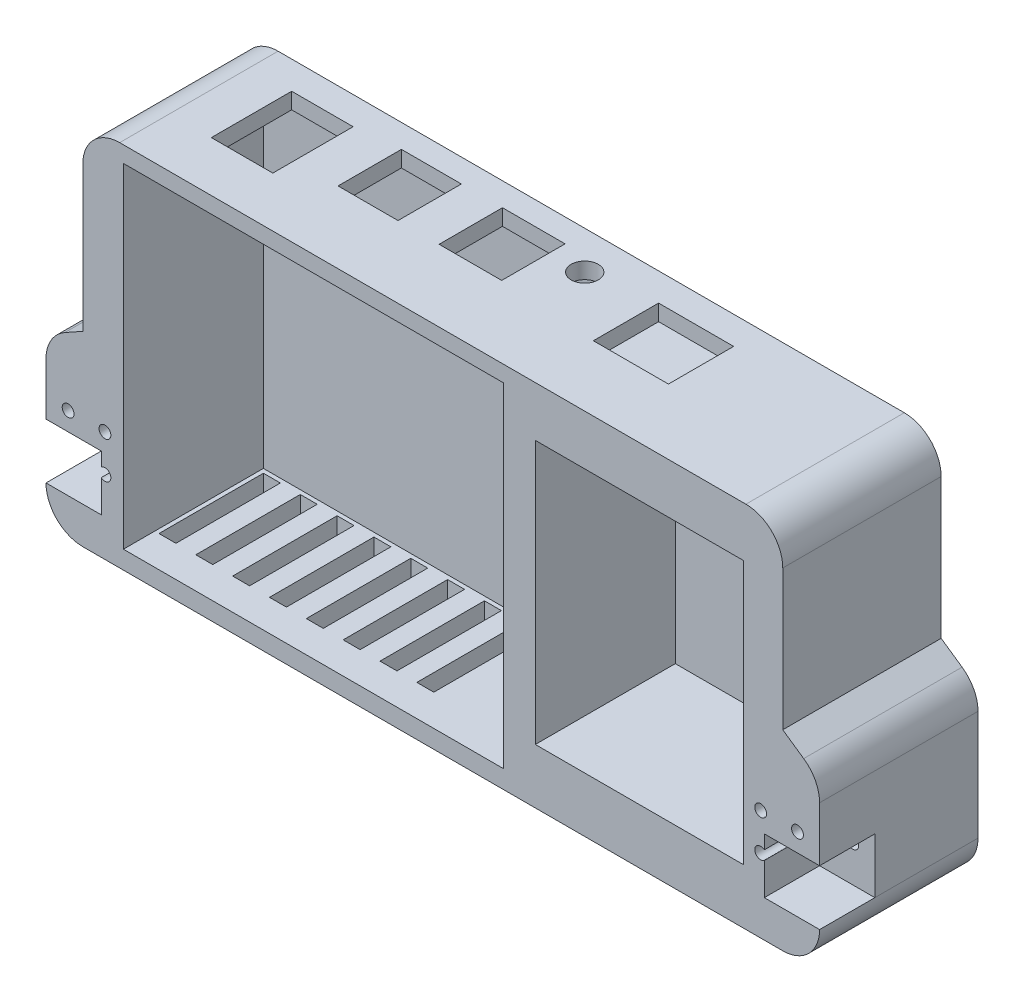
SolidWorks part; units mm, degrees
material "ABS"
ref_plane "前视基准面" through (0, 0, 0) normal (0, 0, 1) x (1, 0, 0)
ref_plane "上视基准面" through (0, 0, 0) normal (0, 1, 0) x (1, 0, 0)
ref_plane "右视基准面" through (0, 0, 0) normal (1, 0, 0) x (0, 0, -1)
other "Configuration Table"
sketch "草图1" plane through (0, 0, 0) normal (0, 0, 1) x (1, 0, 0)
  line L0 (0, 10) -> (0, 39.1866)
  line L1 (5.1248, 47.9177) -> (10, 50.6399)
  line L2 (10, 50.6399) -> (10, 90)
  line L3 (20, 100) -> (190, 100)
  line L4 (200, 90) -> (200, 51.9634)
  line L5 (200, 51.9634) -> (205.6833, 48.0378)
  line L6 (210, 39.8098) -> (210, 10)
  line L7 (200, 0) -> (10, 0)
  line L9 (21.0146, 95.6225) -> (124.2146, 95.6225)
  line L10 (21.0146, 95.6225) -> (21.0146, 4.9225)
  line L11 (21.0146, 4.9225) -> (124.2146, 4.9225)
  line L12 (124.2146, 95.6225) -> (124.2146, 4.9225)
  line L13 (132.8291, 86.4254) -> (189.3291, 86.4254)
  line L14 (132.8291, 86.4254) -> (132.8291, 14.9254)
  line L15 (132.8291, 14.9254) -> (189.3291, 14.9254)
  line L16 (189.3291, 86.4254) -> (189.3291, 14.9254)
  arc A0 (210, 10) -> (200, 0) centre (200, 10) cw
  arc A1 (0, 10) -> (10, 0) centre (10, 10) ccw
  arc A2 (205.6833, 48.0378) -> (210, 39.8098) centre (200, 39.8098) cw
  arc A3 (0, 39.1866) -> (5.1248, 47.9177) centre (10, 39.1866) cw
  arc A4 (190, 100) -> (200, 90) centre (190, 90) cw
  arc A5 (10, 90) -> (20, 100) centre (20, 90) cw
  point P13 (0, 0)
  dimension "D1" = 10
  dimension "D2" = 190
  dimension "D3" = 100
  dimension "D4" = 103.2
  dimension "D5" = 90.7
  dimension "D6" = 71.5
  dimension "D7" = 56.5
  dimension "D8" = 10
  dimension "D9" = 10
extrude "凸台-拉伸1" add sketch "草图1" along normal blind 43
sketch "草图3" plane through (0, 0, 0) normal (0, 0, 1) x (1, 0, 0)
  line L0 (0, 10) -> (0, 39.1866)
  line L1 (5.1248, 47.9177) -> (10, 50.6399)
  line L2 (10, 50.6399) -> (10, 90)
  line L3 (20, 100) -> (180, 100)
  line L4 (190, 90) -> (190, 51.9634)
  line L5 (190, 51.9634) -> (195.6833, 48.0378)
  line L6 (200, 39.8098) -> (200, 10)
  line L7 (190, 0) -> (10, 0)
  arc A0 (200, 10) -> (190, 0) centre (190, 10) cw
  arc A1 (0, 10) -> (10, 0) centre (10, 10) ccw
  arc A2 (195.6833, 48.0378) -> (200, 39.8098) centre (190, 39.8098) cw
  arc A3 (0, 39.1866) -> (5.1248, 47.9177) centre (10, 39.1866) cw
  arc A4 (180, 100) -> (190, 90) centre (180, 90) cw
  arc A5 (10, 90) -> (20, 100) centre (20, 90) cw
  point P13 (0, 0)
  dimension "D1" = 10
  dimension "D2" = 180
  dimension "D3" = 100
  dimension "D8" = 10
  dimension "D9" = 10
extrude "凸台-拉伸3" add sketch "草图3" along normal blind 5
sketch "草图4" plane through (0, 100, 0) normal (0, 1, 0) x (1, 0, 0)
  line L1 (130.8683, -7.5722) -> (151.2394, -7.5722)
  line L2 (130.8683, -7.5722) -> (130.8683, -25.2818)
  line L3 (130.8683, -25.2818) -> (151.2394, -25.2818)
  line L4 (151.2394, -7.5722) -> (151.2394, -25.2818)
  line L5 (31.2602, -7.5722) -> (47.9461, -7.5722)
  line L6 (31.2602, -7.5722) -> (31.2602, -29.3765)
  line L7 (31.2602, -29.3765) -> (47.9461, -29.3765)
  line L8 (47.9461, -7.5722) -> (47.9461, -29.3765)
  line L9 (59.8207, -6.3438) -> (76.0972, -6.3438)
  line L10 (59.8207, -6.3438) -> (59.8207, -23.5415)
  line L11 (59.8207, -23.5415) -> (76.0972, -23.5415)
  line L12 (76.0972, -6.3438) -> (76.0972, -23.5415)
  line L13 (87.2552, -6.3438) -> (104.2483, -6.3438)
  line L14 (87.2552, -6.3438) -> (87.2552, -23.5415)
  line L15 (87.2552, -23.5415) -> (104.2483, -23.5415)
  line L16 (104.2483, -6.3438) -> (104.2483, -23.5415)
  circle A0 centre (113.5637, -10.3226) radius 3.6826
extrude "切除-拉伸2" cut sketch "草图4" against normal up to surface (4.3775 mm away) up to face at (72.6146, 95.6225, 24)
sketch "草图5" plane through (0, 0, 0) normal (0, -1, 0) x (1, 0, 0)
  line L0 (32.1495, 34.485) -> (32.1495, 6.1292)
  line L1 (22.1495, 34.485) -> (26.756, 34.485)
  line L2 (22.1495, 34.485) -> (22.1495, 6.1292)
  line L3 (22.1495, 6.1292) -> (26.756, 6.1292)
  line L4 (26.756, 34.485) -> (26.756, 6.1292)
  line L5 (32.1495, 34.485) -> (36.756, 34.485)
  line L6 (36.756, 34.485) -> (36.756, 6.1292)
  line L7 (32.1495, 6.1292) -> (36.756, 6.1292)
  line L8 (42.1495, 34.485) -> (42.1495, 6.1292)
  line L9 (42.1495, 34.485) -> (46.756, 34.485)
  line L10 (46.756, 34.485) -> (46.756, 6.1292)
  line L11 (42.1495, 6.1292) -> (46.756, 6.1292)
  line L12 (52.1495, 34.485) -> (52.1495, 6.1292)
  line L13 (52.1495, 34.485) -> (56.756, 34.485)
  line L14 (56.756, 34.485) -> (56.756, 6.1292)
  line L15 (52.1495, 6.1292) -> (56.756, 6.1292)
  line L16 (62.1495, 34.485) -> (62.1495, 6.1292)
  line L17 (62.1495, 34.485) -> (66.756, 34.485)
  line L18 (66.756, 34.485) -> (66.756, 6.1292)
  line L19 (62.1495, 6.1292) -> (66.756, 6.1292)
  line L20 (72.1495, 34.485) -> (72.1495, 6.1292)
  line L21 (72.1495, 34.485) -> (76.756, 34.485)
  line L22 (76.756, 34.485) -> (76.756, 6.1292)
  line L23 (72.1495, 6.1292) -> (76.756, 6.1292)
  line L24 (82.1495, 34.485) -> (82.1495, 6.1292)
  line L25 (82.1495, 34.485) -> (86.756, 34.485)
  line L26 (86.756, 34.485) -> (86.756, 6.1292)
  line L27 (82.1495, 6.1292) -> (86.756, 6.1292)
  line L28 (92.1495, 34.485) -> (92.1495, 6.1292)
  line L29 (92.1495, 34.485) -> (96.756, 34.485)
  line L30 (96.756, 34.485) -> (96.756, 6.1292)
  line L31 (92.1495, 6.1292) -> (96.756, 6.1292)
  dimension "D1" = 8
extrude "切除-拉伸3" cut sketch "草图5" against normal up to surface (4.9225 mm away) up to face at (72.6146, 4.9225, 24)
sketch "草图7" plane through (0, 0, 43) normal (0, 0, 1) x (1, 0, 0)
  line L0 (6, 30) -> (16, 30) construction
  line L1 (6, 30) -> (6, 20) construction
  line L2 (0, 39.1866) -> (0, 10) construction
  line L3 (10, 0) -> (200, 0) construction
  line L4 (210, 10) -> (210, 39.8098) construction
  line L6 (194, 30) -> (204, 30) construction
  line L7 (194, 30) -> (194, 20) construction
  circle A11 centre (6, 30) radius 1.6
  circle A12 centre (16, 30) radius 1.6
  circle A13 centre (16, 20) radius 1.6
  circle A14 centre (6, 20) radius 1.6
  circle A19 centre (194, 30) radius 1.6
  circle A20 centre (204, 30) radius 1.6
  circle A21 centre (204, 20) radius 1.6
  circle A22 centre (194, 20) radius 1.6
  dimension "D1" = 3.2
  dimension "D4" = 6
  dimension "D6" = 30
  dimension "D9" = 3.2
  dimension "D2" = 10
  dimension "D3" = 10
  dimension "D5" = 30
  dimension "D7" = 6
  dimension "D8" = 10
  dimension "D10" = 10
  dimension "D11" = 10
extrude "切除-拉伸4" cut sketch "草图7" against normal through all
sketch "草图8" plane through (0, 0, 0) normal (-1, 0, 0) x (0, 0, 1)
  line L0 (43, 10) -> (0, 10) construction
  line L1 (28, 25) -> (43, 25)
  line L2 (28, 25) -> (28, 10)
  line L3 (28, 10) -> (43, 10)
  line L4 (43, 25) -> (43, 10)
  dimension "D1" = 15
  dimension "D2" = 15
extrude "切除-拉伸5" cut sketch "草图8" against normal blind 15
ref_plane "基准面1" through (105, 0, 0) normal (-1, 0, 0) x (0, 0, 1)
mirror "镜向1" about plane through (105, 0, 0) normal (-1, 0, 0) of "切除-拉伸5"
